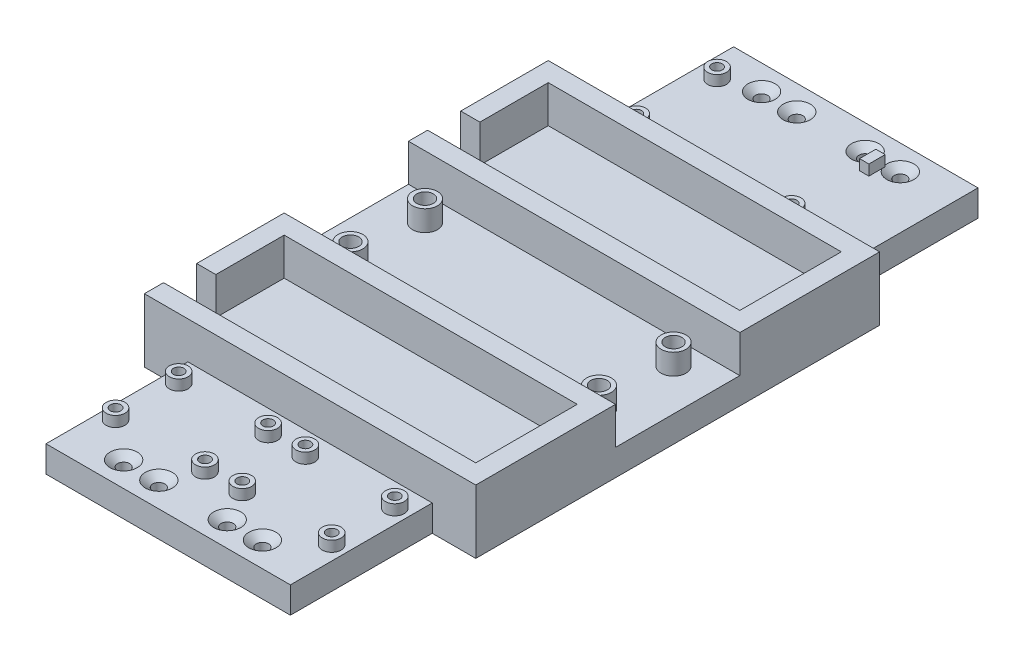
SolidWorks part; units mm, degrees
ref_plane "Front Plane" through (0, 0, 0) normal (0, 0, 1) x (1, 0, 0)
ref_plane "Top Plane" through (0, 0, 0) normal (0, 1, 0) x (1, 0, 0)
ref_plane "Right Plane" through (0, 0, 0) normal (1, 0, 0) x (0, 0, -1)
sketch "Sketch2" plane through (0, 0, 0) normal (0, 1, 0) x (1, 0, 0)
  line L1 (40, -83) -> (-40, -83)
  line L2 (40, -83) -> (40, 83)
  line L3 (40, 83) -> (-40, 83)
  line L4 (-40, -83) -> (-40, 83)
  line L5 (40, -83) -> (-40, 83) construction
  line L6 (40, 83) -> (-40, -83) construction
  point P0 (0, 0)
  dimension "D1" = 80
  dimension "D2" = 166
extrude "Boss-Extrude1" add sketch "Sketch2" along normal blind 6.35
sketch "Sketch3" plane through (0, 6.35, 0) normal (0, 1, 0) x (1, 0, 0)
  line L3 (16.755, 77) -> (8.255, 77)
  line L4 (0, 0) -> (0, 77)
  line L6 (0, 77) -> (8.255, 77)
  dimension "D1" = 8.255
  dimension "D2" = 8.5
  dimension "D3" = 77
hole_wizard "CSK for #4 Flat Head Machine Screw (100)1" positions "Sketch4" profile "Sketch5" countersink size "#4" standard "ANSI Inch" end condition through all
sketch "Sketch4" plane through (0, 6.35, 0) normal (0, 1, 0) x (1, 0, 0)
  point P0 (16.755, 77)
  point P3 (8.255, 77)
sketch "Sketch5" plane through (16.755, 6.35, -77) normal (1, 0, 0) x (0, 0, 1)
  line L0 (0, 0) -> (0, 6.35)
  line L1 (0, 6.35) -> (1.4732, 6.35)
  line L2 (1.4732, 6.35) -> (1.4732, 1.5116)
  line L3 (1.4732, 1.5116) -> (3.2747, 0)
  line L5 (3.2747, 0) -> (0, 0)
  line L6 (-1.4732, 1.5116) -> (-3.2747, 0) construction
  line L11 (0, -6.35) -> (0, 107.95) construction
  dimension "Thru Hole Dia." = 2.9464
  dimension "Thru Hole Depth" = 6.35
  dimension "Near C'Sink Dia." = 6.5493
  dimension "Near C'Sink Angle" = 100
mirror "Mirror1" about plane through (0, 0, 0) normal (0, 0, 1) of "CSK for #4 Flat Head Machine Screw (100)1"
mirror "Mirror2" about plane through (0, 0, 0) normal (1, 0, 0) of "Mirror1", "CSK for #4 Flat Head Machine Screw (100)1"
sketch "Sketch7" plane through (0, 6.35, 0) normal (0, 1, 0) x (1, 0, 0)
  line L0 (-30, 9) -> (30, 9)
  line L1 (30, 9) -> (30, -9)
  line L2 (30, -9) -> (-30, -9)
  line L3 (-30, -9) -> (-30, 9)
  line L4 (-4.5, -69.62) -> (-26.09, -69.62)
  line L5 (-26.09, -69.62) -> (-26.09, -54.38)
  line L6 (-26.09, -54.38) -> (-4.5, -54.38)
  line L7 (-4.5, -54.38) -> (-4.5, -69.62)
  line L8 (4.5, -69.62) -> (4.5, -54.38)
  line L9 (4.5, -54.38) -> (26.09, -54.38)
  line L10 (26.09, -54.38) -> (26.09, -69.62)
  line L11 (26.09, -69.62) -> (4.5, -69.62)
  line L13 (0, -9) -> (0, 0) construction
  line L14 (-24.75, 54.75) -> (12.75, 54.75)
  line L15 (12.75, 54.75) -> (12.75, 74.25)
  line L16 (12.75, 74.25) -> (-24.75, 74.25)
  line L17 (-24.75, 74.25) -> (-24.75, 54.75)
  line L18 (12.75, 64.5) -> (0, 64.5)
  line L19 (0, 0) -> (-30, 0) construction
  line L20 (-4.5, -62) -> (4.5, -62) construction
  line L21 (0, -62) -> (0, -9) construction
  line L22 (0, 64.5) -> (0, 0) construction
  point P14 (4.5, -62)
  dimension "D2" = 64.5
  dimension "D3" = 21.59
  dimension "D4" = 15.24
  dimension "D5" = 18
  dimension "D6" = 19.5
  dimension "D7" = 15.24
  dimension "D8" = 37.5
  dimension "D9" = 9
  dimension "D10" = 60
  dimension "D11" = 53
  dimension "D12" = 12.75
sketch "Sketch9" plane through (0, 6.35, 0) normal (0, 1, 0) x (1, 0, 0)
  circle A0 centre (-30, 9) radius 2
  circle A1 centre (-30, -9) radius 2
  circle A2 centre (30, -9) radius 2
  circle A3 centre (30, 9) radius 2
  circle A4 centre (-30, -9) radius 3
  circle A5 centre (-30, 9) radius 3
  circle A6 centre (30, 9) radius 3
  circle A7 centre (30, -9) radius 3
  dimension "D1" = 4
  dimension "D2" = 1
extrude "Boss-Extrude3" add sketch "Sketch9" along normal blind 5
sketch "Sketch15" plane through (0, 6.35, 0) normal (0, 1, 0) x (1, 0, 0)
  line L0 (-35.375, 44.125) -> (35.375, 44.125)
  line L1 (35.375, 44.125) -> (35.375, 19.625)
  line L2 (35.375, 19.625) -> (-40, 19.625)
  line L3 (-35.375, 27.625) -> (-35.375, 44.125)
  line L4 (35.375, 31.875) -> (40, 31.875) construction
  line L5 (40, 15) -> (-40, 15)
  line L6 (-40, 83) -> (-40, -83) construction
  line L7 (40, -83) -> (40, 83) construction
  line L8 (-40, 15) -> (-40, 19.625)
  line L9 (-40, 48.75) -> (40, 48.75)
  line L10 (40, 48.75) -> (40, 15)
  line L11 (-35.375, 27.625) -> (-40, 27.625)
  line L13 (-40, 27.625) -> (-40, 48.75)
  line L14 (0, 48.75) -> (0, 44.125) construction
  line L15 (0, 15) -> (0, 19.625) construction
  line L16 (0, 15) -> (0, 0) construction
  line L17 (0, 0) -> (0, -15) construction
  line L18 (-40, -15) -> (40, -15)
  line L19 (40, -15) -> (40, -48.75)
  line L20 (40, -48.75) -> (-40, -48.75)
  line L21 (-40, -48.75) -> (-40, -44.125)
  line L22 (-40, -44.125) -> (35.375, -44.125)
  line L23 (35.375, -44.125) -> (35.375, -19.625)
  line L24 (35.375, -19.625) -> (-35.375, -19.625)
  line L25 (-35.375, -19.625) -> (-35.375, -36.125)
  line L26 (-35.375, -36.125) -> (-40, -36.125)
  line L27 (-40, -36.125) -> (-40, -15)
  line L28 (0, -15) -> (0, -19.625) construction
  point P35 (0, -15)
  dimension "D1" = 70.75
  dimension "D2" = 24.5
  dimension "D3" = 15
  dimension "D4" = 8
extrude "Boss-Extrude5" add sketch "Sketch15" along normal blind 9
sketch "Sketch10" plane through (0, 6.35, 0) normal (0, 1, 0) x (1, 0, 0)
  line L1 (11.625, 72.2784) -> (13.875, 72.2784)
  line L2 (11.625, 72.2784) -> (11.625, 76.2216)
  line L3 (11.625, 76.2216) -> (13.875, 76.2216)
  line L4 (13.875, 72.2784) -> (13.875, 76.2216)
  line L5 (11.625, 72.2784) -> (13.875, 76.2216) construction
  line L6 (11.625, 76.2216) -> (13.875, 72.2784) construction
  circle A0 centre (-4.5, -54.38) radius 1.27
  circle A1 centre (-4.5, -69.62) radius 1.27
  circle A2 centre (-26.09, -69.62) radius 1.27
  circle A3 centre (-26.09, -54.38) radius 1.27
  circle A4 centre (4.5, -54.38) radius 1.27
  circle A5 centre (4.5, -69.62) radius 1.27
  circle A6 centre (26.09, -69.62) radius 1.27
  circle A7 centre (26.09, -54.38) radius 1.27
  circle A8 centre (-4.5, -54.38) radius 2.27
  circle A9 centre (-4.5, -69.62) radius 2.27
  circle A10 centre (-26.09, -54.38) radius 2.27
  circle A11 centre (-26.09, -69.62) radius 2.27
  circle A12 centre (4.5, -54.38) radius 2.27
  circle A13 centre (4.5, -69.62) radius 2.27
  circle A14 centre (26.09, -69.62) radius 2.27
  circle A15 centre (26.09, -54.38) radius 2.27
  circle A16 centre (12.75, 54.75) radius 1.27
  circle A17 centre (12.75, 54.75) radius 2.27
  circle A18 centre (12.75, 74.25) radius 1.27 construction
  circle A19 centre (12.75, 74.25) radius 2.27 construction
  circle A20 centre (-24.75, 74.25) radius 1.27
  circle A21 centre (-24.75, 54.75) radius 1.27
  circle A22 centre (-24.75, 54.75) radius 2.27
  circle A23 centre (-24.75, 74.25) radius 2.27
  dimension "D1" = 2.54
  dimension "D2" = 1
  dimension "D3" = 2.25
extrude "Boss-Extrude4" add sketch "Sketch10" along normal blind 2.54
sketch "Sketch11" plane through (0, 6.35, 0) normal (0, 1, 0) x (1, 0, 0)
  circle A0 centre (-30, -9) radius 2
  circle A1 centre (-30, 9) radius 2
  circle A2 centre (26.09, -54.38) radius 1.27
  circle A3 centre (26.09, -69.62) radius 1.27
  circle A4 centre (4.5, -54.38) radius 1.27
  circle A5 centre (4.5, -69.62) radius 1.27
  circle A6 centre (30, 9) radius 2
  circle A7 centre (30, -9) radius 2
  circle A8 centre (-26.09, -69.62) radius 1.27
  circle A9 centre (-26.09, -54.38) radius 1.27
  circle A10 centre (-4.5, -69.62) radius 1.27
  circle A11 centre (-4.5, -54.38) radius 1.27
  circle A12 centre (-30, -9) radius 2 construction
  circle A13 centre (-4.5, -54.38) radius 1.27 construction
  circle A14 centre (12.75, 74.25) radius 1.27 construction
  circle A15 centre (12.75, 54.75) radius 1.27
  circle A16 centre (-24.75, 54.75) radius 1.27
  circle A17 centre (-24.75, 74.25) radius 1.27
extrude "Cut-Extrude1" cut sketch "Sketch11" against normal through all
sketch "Sketch12" plane through (0, 0, 0) normal (0, -1, 0) x (1, 0, 0)
  line L1 (-23.59, 52.9366) -> (-23.59, 55.8234)
  line L2 (-23.59, 55.8234) -> (-26.09, 57.2668)
  line L3 (-26.09, 57.2668) -> (-28.59, 55.8234)
  line L4 (-28.59, 55.8234) -> (-28.59, 52.9366)
  line L5 (-28.59, 52.9366) -> (-26.09, 51.4932)
  line L6 (-26.09, 51.4932) -> (-23.59, 52.9366)
  line L7 (-2, 52.9366) -> (-2, 55.8234)
  line L8 (-2, 55.8234) -> (-4.5, 57.2668)
  line L9 (-4.5, 57.2668) -> (-7, 55.8234)
  line L10 (-7, 55.8234) -> (-7, 52.9366)
  line L11 (-7, 52.9366) -> (-4.5, 51.4932)
  line L12 (-4.5, 51.4932) -> (-2, 52.9366)
  line L13 (-23.59, 68.1766) -> (-23.59, 71.0634)
  line L14 (-23.59, 71.0634) -> (-26.09, 72.5068)
  line L15 (-26.09, 72.5068) -> (-28.59, 71.0634)
  line L16 (-28.59, 71.0634) -> (-28.59, 68.1766)
  line L17 (-28.59, 68.1766) -> (-26.09, 66.7332)
  line L18 (-26.09, 66.7332) -> (-23.59, 68.1766)
  line L19 (-2, 68.1766) -> (-2, 71.0634)
  line L20 (-2, 71.0634) -> (-4.5, 72.5068)
  line L21 (-4.5, 72.5068) -> (-7, 71.0634)
  line L22 (-7, 71.0634) -> (-7, 68.1766)
  line L23 (-7, 68.1766) -> (-4.5, 66.7332)
  line L24 (-4.5, 66.7332) -> (-2, 68.1766)
  line L25 (7, 52.9366) -> (7, 55.8234)
  line L26 (7, 55.8234) -> (4.5, 57.2668)
  line L27 (4.5, 57.2668) -> (2, 55.8234)
  line L28 (2, 55.8234) -> (2, 52.9366)
  line L29 (2, 52.9366) -> (4.5, 51.4932)
  line L30 (4.5, 51.4932) -> (7, 52.9366)
  line L31 (7, 68.1766) -> (7, 71.0634)
  line L32 (7, 71.0634) -> (4.5, 72.5068)
  line L33 (4.5, 72.5068) -> (2, 71.0634)
  line L34 (2, 71.0634) -> (2, 68.1766)
  line L35 (2, 68.1766) -> (4.5, 66.7332)
  line L36 (4.5, 66.7332) -> (7, 68.1766)
  line L37 (28.59, 68.1766) -> (28.59, 71.0634)
  line L38 (28.59, 71.0634) -> (26.09, 72.5068)
  line L39 (26.09, 72.5068) -> (23.59, 71.0634)
  line L40 (23.59, 71.0634) -> (23.59, 68.1766)
  line L41 (23.59, 68.1766) -> (26.09, 66.7332)
  line L42 (26.09, 66.7332) -> (28.59, 68.1766)
  line L43 (28.59, 52.9366) -> (28.59, 55.8234)
  line L44 (28.59, 55.8234) -> (26.09, 57.2668)
  line L45 (26.09, 57.2668) -> (23.59, 55.8234)
  line L46 (23.59, 55.8234) -> (23.59, 52.9366)
  line L47 (23.59, 52.9366) -> (26.09, 51.4932)
  line L48 (26.09, 51.4932) -> (28.59, 52.9366)
  line L49 (-22.25, -75.6934) -> (-22.25, -72.8066)
  line L50 (-22.25, -72.8066) -> (-24.75, -71.3632)
  line L51 (-24.75, -71.3632) -> (-27.25, -72.8066)
  line L52 (-27.25, -72.8066) -> (-27.25, -75.6934)
  line L53 (-27.25, -75.6934) -> (-24.75, -77.1368)
  line L54 (-24.75, -77.1368) -> (-22.25, -75.6934)
  line L55 (-22.25, -56.1934) -> (-22.25, -53.3066)
  line L56 (-22.25, -53.3066) -> (-24.75, -51.8632)
  line L57 (-24.75, -51.8632) -> (-27.25, -53.3066)
  line L58 (-27.25, -53.3066) -> (-27.25, -56.1934)
  line L59 (-27.25, -56.1934) -> (-24.75, -57.6368)
  line L60 (-24.75, -57.6368) -> (-22.25, -56.1934)
  line L61 (15.4277, -75.6934) -> (15.4277, -72.8066) construction
  line L62 (15.4277, -72.8066) -> (12.9277, -71.3632) construction
  line L63 (12.9277, -71.3632) -> (10.4277, -72.8066) construction
  line L64 (10.4277, -72.8066) -> (10.4277, -75.6934) construction
  line L65 (10.4277, -75.6934) -> (12.9277, -77.1368) construction
  line L66 (12.9277, -77.1368) -> (15.4277, -75.6934) construction
  line L67 (15.25, -56.1934) -> (15.25, -53.3066)
  line L68 (15.25, -53.3066) -> (12.75, -51.8632)
  line L69 (12.75, -51.8632) -> (10.25, -53.3066)
  line L70 (10.25, -53.3066) -> (10.25, -56.1934)
  line L71 (10.25, -56.1934) -> (12.75, -57.6368)
  line L72 (12.75, -57.6368) -> (15.25, -56.1934)
  circle A0 centre (-26.09, 54.38) radius 2.5 construction
  circle A1 centre (-4.5, 54.38) radius 2.5 construction
  circle A2 centre (-26.09, 69.62) radius 2.5 construction
  circle A3 centre (-4.5, 69.62) radius 2.5 construction
  circle A4 centre (4.5, 54.38) radius 2.5 construction
  circle A5 centre (4.5, 69.62) radius 2.5 construction
  circle A6 centre (26.09, 69.62) radius 2.5 construction
  circle A7 centre (26.09, 54.38) radius 2.5 construction
  circle A8 centre (-24.75, -74.25) radius 2.5 construction
  circle A9 centre (-24.75, -54.75) radius 2.5 construction
  circle A10 centre (12.9277, -74.25) radius 2.5 construction
  circle A11 centre (12.75, -54.75) radius 2.5 construction
  dimension "D1" = 5
extrude "Cut-Extrude2" cut sketch "Sketch12" against normal offset from surface (2.89 mm away) 6 up to face at (-26.09, 8.89, 56.65)
sketch "Sketch14" plane through (0, 0, 0) normal (0, -1, 0) x (1, 0, 0)
  line L1 (33.175, 7.1669) -> (33.175, 10.8331)
  line L2 (33.175, 10.8331) -> (30, 12.6662)
  line L3 (30, 12.6662) -> (26.825, 10.8331)
  line L4 (26.825, 10.8331) -> (26.825, 7.1669)
  line L5 (26.825, 7.1669) -> (30, 5.3338)
  line L6 (30, 5.3338) -> (33.175, 7.1669)
  line L7 (26.825, -10.8331) -> (30, -12.6662)
  line L8 (30, -12.6662) -> (33.175, -10.8331)
  line L9 (33.175, -10.8331) -> (33.175, -7.1669)
  line L10 (33.175, -7.1669) -> (30, -5.3338)
  line L11 (30, -5.3338) -> (26.825, -7.1669)
  line L12 (26.825, -7.1669) -> (26.825, -10.8331)
  line L13 (-26.825, 10.8331) -> (-30, 12.6662)
  line L14 (-30, 12.6662) -> (-33.175, 10.8331)
  line L15 (-33.175, 10.8331) -> (-33.175, 7.1669)
  line L16 (-33.175, 7.1669) -> (-30, 5.3338)
  line L17 (-30, 5.3338) -> (-26.825, 7.1669)
  line L18 (-26.825, 7.1669) -> (-26.825, 10.8331)
  line L19 (-33.175, -10.8331) -> (-30, -12.6662)
  line L20 (-30, -12.6662) -> (-26.825, -10.8331)
  line L21 (-26.825, -10.8331) -> (-26.825, -7.1669)
  line L22 (-26.825, -7.1669) -> (-30, -5.3338)
  line L23 (-30, -5.3338) -> (-33.175, -7.1669)
  line L24 (-33.175, -7.1669) -> (-33.175, -10.8331)
  circle A0 centre (30, 9) radius 3.175 construction
  circle A1 centre (30, -9) radius 3.175 construction
  circle A2 centre (-30, 9) radius 3.175 construction
  circle A3 centre (-30, -9) radius 3.175 construction
  dimension "D1" = 6.35
sketch "Sketch16" plane through (0, 6.35, 0) normal (0, 1, 0) x (1, 0, 0)
  line L0 (40, 83) -> (-40, 83) construction
  line L1 (29.5, 83) -> (40, 83)
  line L2 (29.5, 83) -> (29.5, 48.75)
  line L3 (29.5, 48.75) -> (40, 48.75)
  line L4 (40, 83) -> (40, 48.75)
  line L5 (29.5, 83) -> (40, 48.75) construction
  line L6 (29.5, 48.75) -> (40, 83) construction
  line L7 (-29.5, 83) -> (-40, 83)
  line L8 (-29.5, 83) -> (-29.5, 48.75)
  line L9 (-29.5, 48.75) -> (-40, 48.75)
  line L10 (-40, 83) -> (-40, 48.75)
  line L11 (-29.5, 83) -> (-40, 48.75) construction
  line L12 (-29.5, 48.75) -> (-40, 83) construction
  line L13 (-40, -83) -> (40, -83) construction
  line L14 (-29.5, -83) -> (-40, -83)
  line L15 (-29.5, -83) -> (-29.5, -48.75)
  line L16 (-29.5, -48.75) -> (-40, -48.75)
  line L17 (-40, -83) -> (-40, -48.75)
  line L18 (-29.5, -83) -> (-40, -48.75) construction
  line L19 (-29.5, -48.75) -> (-40, -83) construction
  line L20 (29.5, -83) -> (40, -83)
  line L21 (29.5, -83) -> (29.5, -48.75)
  line L22 (29.5, -48.75) -> (40, -48.75)
  line L23 (40, -83) -> (40, -48.75)
  line L24 (29.5, -83) -> (40, -48.75) construction
  line L25 (29.5, -48.75) -> (40, -83) construction
  point P0 (34.75, 65.875)
  point P6 (-34.75, 65.875)
  point P14 (-34.75, -65.875)
  point P20 (34.75, -65.875)
  dimension "D1" = 59
  dimension "D2" = 59
extrude "Cut-Extrude4" cut sketch "Sketch16" against normal through all
extrude "Cut-Extrude3" cut sketch "Sketch14" against normal blind 3.81
